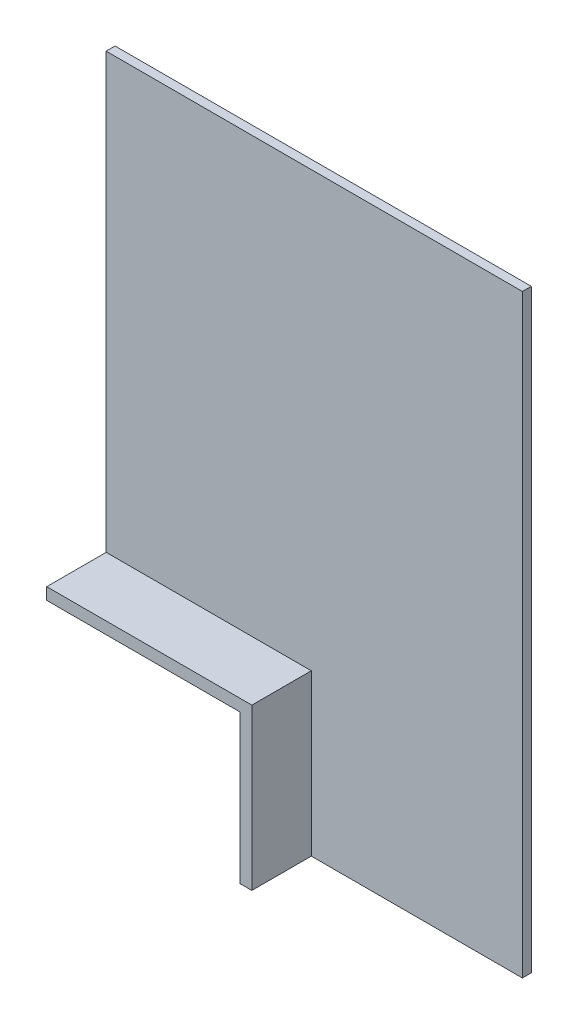
SolidWorks part; units mm, degrees
ref_plane "前视基准面" through (0, 0, 0) normal (0, 0, 1) x (1, 0, 0)
ref_plane "上视基准面" through (0, 0, 0) normal (0, 1, 0) x (1, 0, 0)
ref_plane "右视基准面" through (0, 0, 0) normal (1, 0, 0) x (0, 0, -1)
sketch "草图1" plane through (0, 0, 0) normal (0, 0, 1) x (1, 0, 0)
  line L1 (0, 0) -> (140, 0)
  line L2 (0, 0) -> (0, -200)
  line L3 (0, -200) -> (140, -200)
  line L4 (140, 0) -> (140, -200)
  dimension "D1" = 140
  dimension "D2" = 200
extrude "凸台-拉伸1" add sketch "草图1" along normal blind 3
sketch "草图2" plane through (0, 0, 0) normal (0, 0, -1) x (-1, 0, 0)
  line L0 (0, -200) -> (-140, -200) construction
  line L1 (-65, -200) -> (0, -200)
  line L2 (-65, -200) -> (-65, -150)
  line L3 (-65, -150) -> (0, -150)
  line L4 (0, -200) -> (0, -150)
  line L5 (0, 0) -> (0, -200) construction
  dimension "D1" = 65
  dimension "D2" = 50
extrude "切除-拉伸1" cut sketch "草图2" against normal blind 10
sketch "草图3" plane through (0, 0, 0) normal (0, 0, -1) x (-1, 0, 0)
  line L0 (-65, -200) -> (-140, -200) construction
  line L1 (0, -150) -> (-69, -150)
  line L2 (0, -150) -> (0, -146)
  line L3 (0, -146) -> (-69, -146)
  line L4 (-69, -150) -> (-69, -146)
  line L5 (-69, -200) -> (-65, -200)
  line L6 (-69, -200) -> (-69, -150)
  line L7 (-69, -150) -> (-65, -150)
  line L8 (-65, -200) -> (-65, -150)
  line L9 (-65, -150) -> (-65, -200) construction
  line M3 (-140, -200) -> (-65, -200)
  line M4 (-65, -200) -> (-65, -150)
  line M5 (-65, -150) -> (0, -150)
  line M6 (0, -150) -> (0, 0)
  dimension "D1" = 4
  dimension "D2" = 4
extrude "凸台-拉伸2" add sketch "草图3" against normal blind 23 contours L6 L1 M3 M4 | L4 L1 L3 M5 M6
